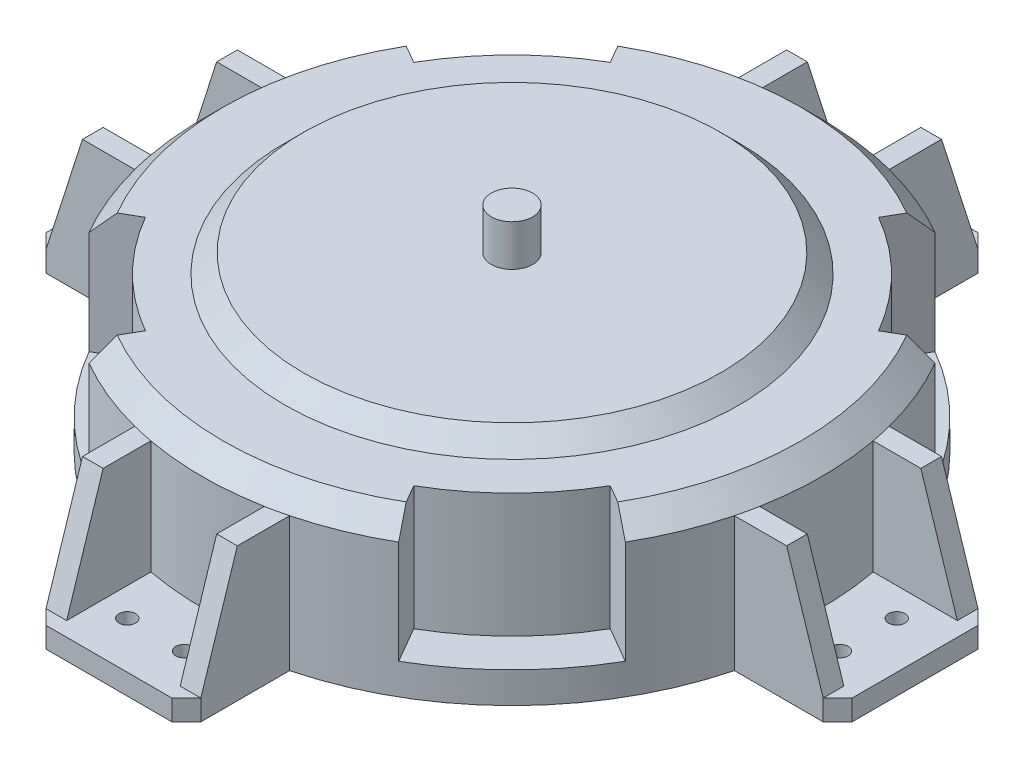
SolidWorks part; units mm, degrees
ref_plane "Front Plane" through (0, 0, 0) normal (0, 0, 1) x (1, 0, 0)
ref_plane "Top Plane" through (0, 0, 0) normal (0, 1, 0) x (1, 0, 0)
ref_plane "Right Plane" through (0, 0, 0) normal (1, 0, 0) x (0, 0, -1)
sketch "Sketch1" plane through (0, 0, 0) normal (0, 1, 0) x (1, 0, 0)
  circle A0 centre (0, 0) radius 150
  dimension "D1" = 300
extrude "Boss-Extrude1" add sketch "Sketch1" along normal blind 75
chamfer "Chamfer1" distance 10 angle 45 1 edges at (0, 75, 150)
sketch "Sketch2" plane through (0, 75, 0) normal (0, 1, 0) x (1, 0, 0)
  line L0 (-149.6047, -10.8824) -> (-195.2369, -10.8824) construction
  line L1 (-195.2369, 37.5) -> (-195.2369, -37.5)
  line L2 (-195.2369, 37.5) -> (-145.2369, 37.5)
  line L3 (-195.2369, -37.5) -> (-145.2369, -37.5)
  circle A1 centre (0, 0) radius 150 construction
  circle A3 centre (0, 0) radius 150 construction
  arc A5 (-145.2369, 37.5) -> (-145.2369, -37.5) centre (0, 0) ccw
  dimension "D1" = 50
  dimension "D2" = 75
extrude "Boss-Extrude3" add sketch "Sketch2" along normal blind 10 from offset 75 offset against normal yes
chamfer "Chamfer2" distance 7 angle 45 2 edges at (-195.2369, 5, -37.5) (-195.2369, 5, 37.5)
sketch "Sketch3" plane through (0, 0, 37.5) normal (0, 0, 1) x (1, 0, 0)
  line L0 (-144.1972, 65) -> (-170.5569, 65)
  line L1 (-170.5569, 65) -> (-188.2369, 10)
  line L2 (-188.2369, 10) -> (-188.2369, 0)
  line L3 (-188.2369, 0) -> (-145.2369, 0)
  line L4 (-188.2369, 0) -> (-145.2369, 0) construction
  line L5 (-145.2369, 0) -> (-144.1972, 65)
  line L6 (-143.2425, 65) -> (-175.5367, 65) construction
  line L7 (-150, 65) -> (150, 65) construction
  dimension "D1" = 17.68
extrude "Boss-Extrude4" add sketch "Sketch3" against normal blind 10
sketch "Sketch4" plane through (0, 75, 0) normal (0, 1, 0) x (1, 0, 0)
  line L0 (-195.2369, 0) -> (-150, 0) construction
  line L1 (-195.2369, 30.5) -> (-195.2369, -30.5) construction
  line L2 (-172.6184, 0) -> (-172.6184, -27.5) construction
  line L3 (-188.2369, -27.5) -> (-147.4576, -27.5) construction
  arc A0 (-145.2369, -37.5) -> (-147.4576, -27.5) centre (0, 0) ccw construction
  circle A1 centre (-172.6184, -13.75) radius 4
  dimension "D1" = 8
extrude "Cut-Extrude1" cut sketch "Sketch4" against normal through all
ref_plane "Plane1" through (0, 0, 0) normal (0, 0, 1) x (1, 0, 0)
mirror "Mirror3" about plane through (0, 0, 0) normal (0, 0, 1) of "Cut-Extrude1", "Boss-Extrude4"
pattern_circular "CirPattern1" count 4 over 360 about axis through (0, 0, 0) along (0, 1, 0) of "Mirror3", "Cut-Extrude1", "Chamfer2", "Boss-Extrude3", "Boss-Extrude4"
sketch "Sketch6" plane through (0, 75, 0) normal (0, 1, 0) x (1, 0, 0)
  line L0 (0, 150) -> (0, -150) construction
  line L1 (-150, 0) -> (0, 0) construction
  line L2 (-112.5833, -65) -> (-129.9038, -75)
  line L3 (-65, -112.5833) -> (-75, -129.9038)
  arc A1 (-129.9038, -75) -> (-75, -129.9038) centre (0, 0) ccw
  circle A2 centre (0, 0) radius 130
  arc A3 (-112.5833, -65) -> (-65, -112.5833) centre (0, 0) ccw
  dimension "D2" = 30
  dimension "D3" = 30
  dimension "D1" = 10
extrude "Cut-Extrude2" cut sketch "Sketch6" against normal blind 60
pattern_circular "CirPattern2" count 4 over 360 about axis through (0, 75, 0) along (0, 1, 0) of "Cut-Extrude2"
sketch "Sketch7" plane through (0, 75, 0) normal (0, 1, 0) x (1, 0, 0)
  circle A0 centre (0, 0) radius 110
  dimension "D1" = 220
extrude "Boss-Extrude5" add sketch "Sketch7" along normal blind 9 draft 45
sketch "Sketch8" plane through (0, 84, 0) normal (0, 1, 0) x (1, 0, 0)
  circle A0 centre (0, 0) radius 10
  dimension "D1" = 20
extrude "Boss-Extrude6" add sketch "Sketch8" along normal blind 20
